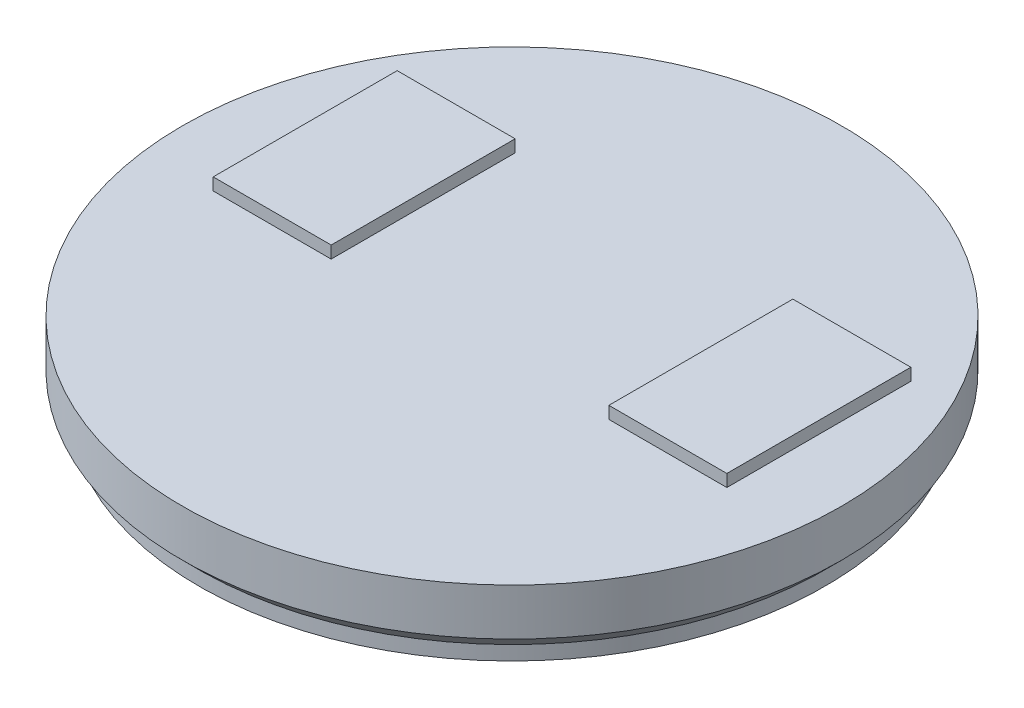
SolidWorks part; units mm, degrees
ref_plane "Front Plane" through (0, 0, 0) normal (0, 0, 1) x (1, 0, 0)
ref_plane "Top Plane" through (0, 0, 0) normal (0, 1, 0) x (1, 0, 0)
ref_plane "Right Plane" through (0, 0, 0) normal (1, 0, 0) x (0, 0, -1)
sketch "Sketch1" plane through (0, 0, 0) normal (0, 0, 1) x (1, 0, 0)
  line L0 (0, 12) -> (0, 15)
  line L1 (0, 15) -> (85, 15)
  line L2 (85, 15) -> (85, 10.5)
  line L3 (85, 10.5) -> (84, 10.5)
  line L4 (77, 3.5) -> (77, 0)
  line L5 (77, 0) -> (71, 0)
  line L6 (71, 0) -> (71, 12)
  line L7 (71, 12) -> (23.75, 12)
  line L8 (84, 10.5) -> (77, 3.5)
  line L9 (0, 12) -> (0, 9)
  line L10 (0, 9) -> (6.5, 9)
  line L11 (6.5, 9) -> (6.5, 6)
  line L12 (6.5, 6) -> (21.25, 6)
  line L13 (21.25, 6) -> (21.25, -7.5)
  line L15 (23.75, -7.5) -> (23.75, 12)
  line L16 (21.25, -7.5) -> (23.75, -7.5)
  point P6 (77, 10.5)
  dimension "D1" = 85
  dimension "D2" = 3
  dimension "D3" = 6
  dimension "D4" = 8
  dimension "D5" = 10.5
  dimension "D6" = 1.5
  dimension "D7" = 21.25
  dimension "D8" = 4.5
  dimension "D10" = 3
  dimension "D11" = 2.5
  dimension "D12" = 13.5
  dimension "D13" = 6.5
  dimension "D14" = 3
  dimension "D15" = 18
  dimension "D16" = 16.5
revolve "Revolve1" add sketch "Sketch1" angle 360 about L9
sketch "Sketch2" plane through (0, 12, 0) normal (0, -1, 0) x (1, 0, 0)
  line L1 (0, 70.2924) -> (-60.875, 35.1462)
  line L2 (-60.875, 35.1462) -> (-60.875, -35.1462)
  line L3 (-60.875, -35.1462) -> (0, -70.2924)
  line L4 (0, -70.2924) -> (60.875, -35.1462)
  line L5 (60.875, -35.1462) -> (60.875, 35.1462)
  line L6 (60.875, 35.1462) -> (0, 70.2924)
  circle A0 centre (0, 0) radius 71 construction
  circle A1 centre (0, 0) radius 71
  circle A2 centre (0, 0) radius 60.875 construction
  circle M8 centre (0, 0) radius 71
  dimension "D1" = 121.75
extrude "Boss-Extrude1" add sketch "Sketch2" along normal blind 11 contours L2 M8 | L1 M8 | L3 M8 | L4 M8 | L5 M8 | L6 M8
sketch "Sketch10" plane through (0, 15, 0) normal (0, 1, 0) x (1, 0, 0)
  line L0 (0, 99.1575) -> (0, -95.7853) construction
  line L1 (-99.194, 0) -> (98.9918, 0) construction
  line L2 (-55, 32) -> (-55, 9) construction
  line L3 (5, 9) -> (43.65, 9) construction
  line L4 (5, 9) -> (5, 32) construction
  line L5 (5, 32) -> (43.65, 32) construction
  line L6 (43.65, 9) -> (43.65, 32) construction
  line L7 (-50, 32) -> (-11.35, 32) construction
  line L8 (-50, 32) -> (-50, 9) construction
  line L9 (-50, 9) -> (-11.35, 9) construction
  line L10 (-11.35, 32) -> (-11.35, 9) construction
  line L11 (-50, 32) -> (-60, 32)
  line L12 (-50, 32) -> (-50, 9)
  line L13 (-50, 9) -> (-60, 9)
  line L14 (-60, 32) -> (-60, 9)
  line L15 (-50, 32) -> (-11.35, 32)
  line L16 (-50, 32) -> (-50, 40)
  line L17 (-50, 40) -> (-11.35, 40)
  line L18 (-11.35, 32) -> (-11.35, 40)
  line L19 (-50, 36) -> (-11.35, 36) construction
  line L20 (5, 32) -> (5, 40)
  line L21 (5, 36) -> (43.65, 36) construction
  line L22 (43.65, 32) -> (43.65, 40)
  line L23 (5, 32) -> (43.65, 32)
  line L24 (5, 40) -> (43.65, 40)
  line L25 (5, 32) -> (43.65, 32) construction
  line L26 (48.65, 32) -> (48.65, 9) construction
  line L27 (53.65, 32) -> (53.65, 9) construction
  line L28 (53.65, 32) -> (53.65, 9)
  line L29 (53.65, 32) -> (43.65, 32)
  line L30 (53.65, 9) -> (43.65, 9)
  line L31 (43.65, 32) -> (43.65, 9)
  line L32 (-49, 40) -> (-49, 32)
  line L33 (42.65, 40) -> (42.65, 32)
  circle A0 centre (-55, 26.5) radius 1.5
  circle A1 centre (-55, 14.5) radius 1.5
  circle A2 centre (-41, 36) radius 1.5
  circle A3 centre (-19.35, 36) radius 1.5
  circle A4 centre (13, 36) radius 1.5
  circle A5 centre (34.65, 36) radius 1.5
  circle A6 centre (48.65, 14.5) radius 1.5
  circle A7 centre (48.65, 26.5) radius 1.5
  circle A8 centre (0, 0) radius 81
  circle A9 centre (0, 0) radius 85
  circle M32 centre (0, 0) radius 85
  dimension "D11" = 3
  dimension "D12" = 5.5
  dimension "D14" = 3
  dimension "D19" = 3
  dimension "D22" = 3
  dimension "D1" = 23
  dimension "D2" = 38.65
  dimension "D3" = 40
  dimension "D4" = 5
  dimension "D5" = 16.35
  dimension "D6" = 23
  dimension "D7" = 38.65
  dimension "D9" = 10
  dimension "D10" = 8
  dimension "D13" = 5.5
  dimension "D15" = 8
  dimension "D16" = 8
  dimension "D17" = 8
  dimension "D18" = 8
  dimension "D20" = 10
  dimension "D21" = 5.5
  dimension "D23" = 5.5
  dimension "D24" = 1
  dimension "D25" = 1
sketch "Sketch12" plane through (0, 12, 0) normal (0, -1, 0) x (1, 0, 0)
  circle A0 centre (0, 0) radius 57.5
  circle A1 centre (0, 0) radius 23.75 construction
  circle A2 centre (0, 0) radius 23.75
  dimension "D1" = 115
extrude "Cut-Extrude8" cut sketch "Sketch12" against normal blind 1
extrude "Cut-Extrude9" cut sketch "Sketch10" against normal blind 10 contours A8 M32
sketch "Sketch14" plane through (0, 13, 0) normal (0, -1, 0) x (-1, 0, 0)
  circle A0 centre (0, 0) radius 23.75
  circle A1 centre (0, 0) radius 57.5
extrude "Boss-Extrude2" add sketch "Sketch14" against normal blind 1
sketch "Sketch15" plane through (0, 15, 0) normal (0, 1, 0) x (1, 0, 0)
  circle A1 centre (0, 0) radius 81
extrude "Boss-Extrude3" add sketch "Sketch15" along normal blind 4
sketch "Sketch16" plane through (0, 13, 0) normal (0, -1, 0) x (1, 0, 0)
  circle A0 centre (0, 0) radius 23.75
  circle A1 centre (0, 0) radius 57.5
extrude "Cut-Extrude11" cut sketch "Sketch16" against normal blind 2
sketch "Sketch17" plane through (0, 19, 0) normal (0, 1, 0) x (1, 0, 0)
  line L0 (-81, 0) -> (81, 0) construction
  line L1 (81, 0) -> (93.3398, 0) construction
  line L3 (-30.2086, 56.7255) -> (29.7914, 56.7255) construction
  line L4 (-30.2086, 56.7255) -> (-30.2086, -43.2745) construction
  line L5 (-30.2086, -43.2745) -> (29.7914, -43.2745) construction
  line L6 (29.7914, 56.7255) -> (29.7914, -43.2745) construction
  line L7 (-34.3336, 0) -> (-63.3336, 0)
  line L8 (33.9164, -10.11) -> (33.9164, 0)
  line L9 (33.9164, 0) -> (62.9164, 0)
  line L10 (62.9164, 0) -> (62.9164, -10.11)
  line L11 (62.9164, -10.11) -> (33.9164, -10.11)
  line L12 (-34.3336, 0) -> (-34.3336, -10.11)
  line L13 (-34.3336, -10.11) -> (-63.3336, -10.11)
  line L14 (-63.3336, -10.11) -> (-63.3336, 0)
  line L15 (-63.3336, 0) -> (-34.3336, 0)
  line L16 (-63.3336, 0) -> (-63.3336, 35.11)
  line L17 (-63.3336, 35.11) -> (-34.3336, 35.11)
  line L18 (-34.3336, 0) -> (-34.3336, 35.11)
  line L19 (33.9164, 0) -> (62.9164, 0)
  line L20 (33.9164, 0) -> (33.9164, 35.11)
  line L21 (33.9164, 35.11) -> (62.9164, 35.11)
  line L22 (62.9164, 0) -> (62.9164, 35.11)
  circle A0 centre (0, 0) radius 81 construction
  point P5 (0, 0)
  point P15 (33.9164, -5.055)
  dimension "D1" = 4.125
  dimension "D2" = 60
  dimension "D3" = 4.125
extrude "Boss-Extrude4" add sketch "Sketch17" along normal blind 3 contours L14 L13 L12 L7 | L7 L18 L17 L16 | L11 L10 L9 L8 | L9 L22 L21 L20
